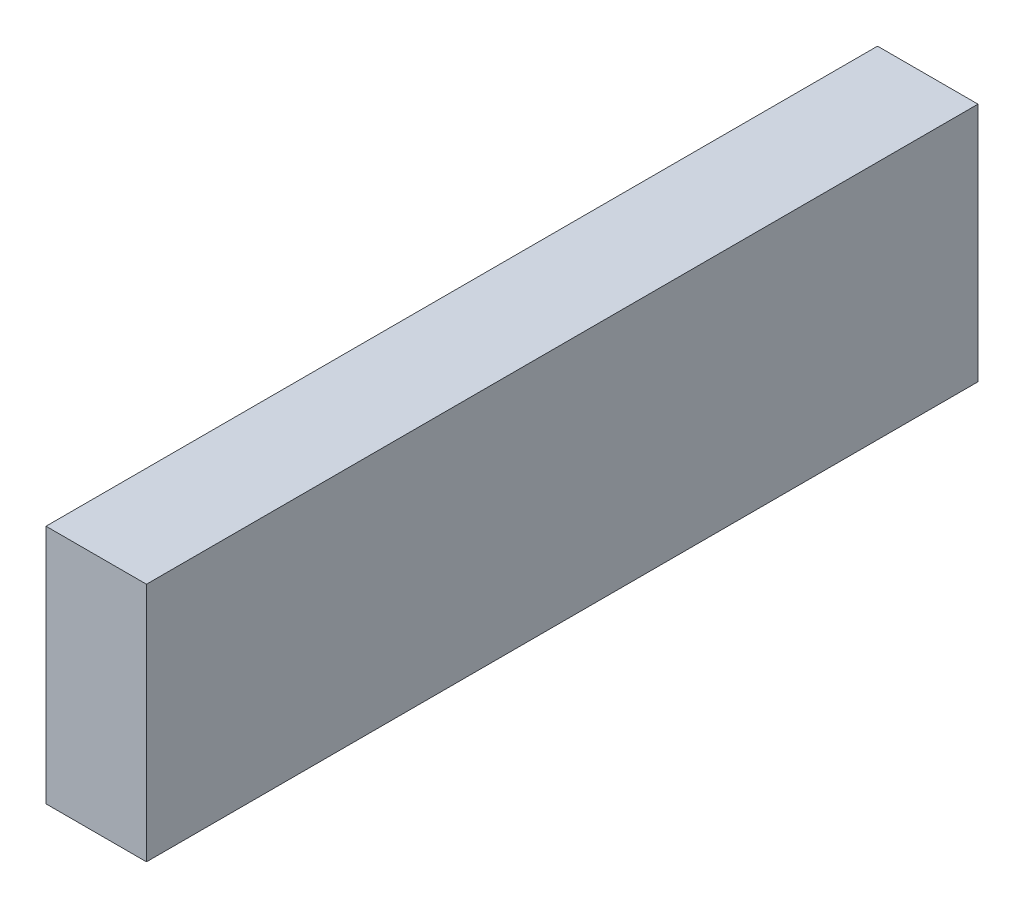
SolidWorks part; units mm, degrees
material "Plain Carbon Steel"
ref_plane "Front Plane" through (0, 0, 0) normal (0, 0, 1) x (1, 0, 0)
ref_plane "Top Plane" through (0, 0, 0) normal (0, 1, 0) x (1, 0, 0)
ref_plane "Right Plane" through (0, 0, 0) normal (1, 0, 0) x (0, 0, -1)
sketch "Sketch1" plane through (0, 0, 0) normal (0, 0, 1) x (1, 0, 0)
  line L1 (0, 0) -> (18.415, 0)
  line L2 (0, 0) -> (0, 44.069)
  line L3 (0, 44.069) -> (18.415, 44.069)
  line L4 (18.415, 0) -> (18.415, 44.069)
  dimension "D1" = 44.069
  dimension "D2" = 18.415
extrude "Boss-Extrude1" add sketch "Sketch1" along normal mid plane 152.4
sketch "Sketch2" plane through (0, 0, 0) normal (1, 0, 0) x (0, 0, -1)
  line L0 (-76.2, 0) -> (-76.2, 44.069) construction
  line L2 (-76.2, 23.876) -> (-49.6062, 23.876) construction
  line L3 (-49.6062, 23.876) -> (49.6062, 23.876) construction
  line L4 (49.6062, 23.876) -> (76.2, 23.876) construction
  line L5 (76.2, 0) -> (76.2, 44.069) construction
  line L6 (-76.2, 44.069) -> (76.2, 44.069) construction
  circle A0 centre (-49.6062, 23.876) radius 9.9187
  circle A1 centre (49.6062, 23.876) radius 9.9187
  dimension "D3" = 19.8374
  dimension "D1" = 26.5938
  dimension "D2" = 20.193
extrude "Cut-Extrude1" cut sketch "Sketch2" along normal blind 12.7
sketch "Sketch3" plane through (12.7, 0, 0) normal (-1, 0, 0) x (0, 0, 1)
  circle A0 centre (49.6062, 23.876) radius 9.525
  circle A1 centre (-49.6062, 23.876) radius 9.525
  dimension "D1" = 19.05
extrude "Boss-Extrude2" add sketch "Sketch3" along normal up to surface (12.7 mm away) up to face at (0, 23.876, 39.6875)
sketch "Sketch4" plane through (0, 0, 0) normal (-1, 0, 0) x (0, 0, 1)
  line L1 (42.2938, 24.4164) -> (45.482, 17.8135)
  line L2 (45.482, 17.8135) -> (52.7944, 17.2731)
  line L3 (52.7944, 17.2731) -> (56.9186, 23.3356)
  line L4 (56.9186, 23.3356) -> (53.7304, 29.9385)
  line L5 (53.7304, 29.9385) -> (46.418, 30.4789)
  line L6 (46.418, 30.4789) -> (42.2938, 24.4164)
  line L7 (-42.2938, 24.4164) -> (-46.418, 30.4789)
  line L8 (-46.418, 30.4789) -> (-53.7304, 29.9385)
  line L9 (-53.7304, 29.9385) -> (-56.9186, 23.3356)
  line L10 (-56.9186, 23.3356) -> (-52.7944, 17.2731)
  line L11 (-52.7944, 17.2731) -> (-45.482, 17.8135)
  line L12 (-45.482, 17.8135) -> (-42.2938, 24.4164)
  circle A0 centre (49.6062, 23.876) radius 6.35 construction
  circle A1 centre (-49.6062, 23.876) radius 6.35 construction
  dimension "D1" = 12.7
extrude "Cut-Extrude2" cut sketch "Sketch4" against normal blind 6.35
chamfer "Chamfer1" distance 0.635 angle 45 2 edges at (0, 23.876, -59.1312) (0, 23.876, 40.0812)
